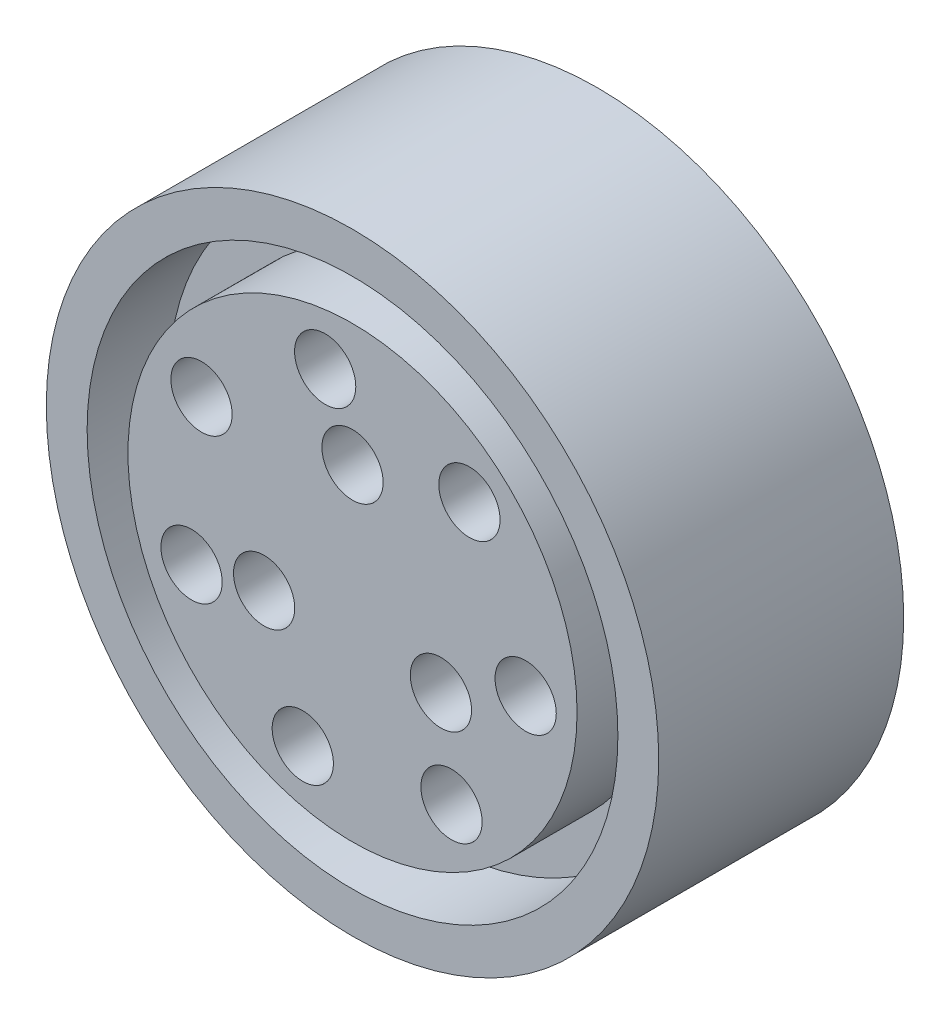
SolidWorks part; units mm, degrees
ref_plane "Front Plane" through (0, 0, 0) normal (0, 0, 1) x (1, 0, 0)
ref_plane "Top Plane" through (0, 0, 0) normal (0, 1, 0) x (1, 0, 0)
ref_plane "Right Plane" through (0, 0, 0) normal (1, 0, 0) x (0, 0, -1)
sketch "Sketch2" plane through (0, 0, 0) normal (0, 0, 1) x (1, 0, 0)
  circle A0 centre (-17.8441, -1.9161) radius 7.5
  dimension "D1" = 15
extrude "Boss-Extrude1" add sketch "Sketch2" along normal blind 6
sketch "Sketch3" plane through (0, 0, 6) normal (0, 0, 1) x (1, 0, 0)
  circle A0 centre (-17.8441, -1.9161) radius 5.5
  circle A1 centre (-17.8441, -1.9161) radius 7.5 construction
  circle A2 centre (-17.8441, -1.9161) radius 6.5
  dimension "D1" = 1
  dimension "D2" = 1
extrude "Cut-Extrude1" cut sketch "Sketch3" against normal blind 2
sketch "Sketch4" plane through (0, 0, 6) normal (0, 0, 1) x (1, 0, 0)
  circle A0 centre (-17.8441, -1.9161) radius 2.5 construction
  circle A1 centre (-17.8441, 0.5839) radius 0.75
  circle A2 centre (-17.8441, -1.9161) radius 5.5 construction
  circle A3 centre (-15.679, -3.1661) radius 0.75
  circle A4 centre (-20.0091, -3.1661) radius 0.75
  circle A5 centre (-17.8441, -1.9161) radius 4.25 construction
  circle A6 centre (-21.5428, 0.1771) radius 0.75
  circle A7 centre (-18.5136, 2.2808) radius 0.75
  circle A8 centre (-14.9802, 1.2241) radius 0.75
  circle A9 centre (-13.6034, -2.1973) radius 0.75
  circle A10 centre (-15.4198, -5.4069) radius 0.75
  circle A11 centre (-19.0618, -5.988) radius 0.75
  circle A12 centre (-21.7868, -3.5028) radius 0.75
  point P27 (-17.8441, -1.9161)
  dimension "D1" = 1.5
  dimension "D2" = 5
  dimension "D3" = 1.5
  dimension "D4" = 7
  dimension "D7" = 8.5
  dimension "D5" = 120
  dimension "D6" = 120
extrude "Cut-Extrude2" cut sketch "Sketch4" against normal blind 2
